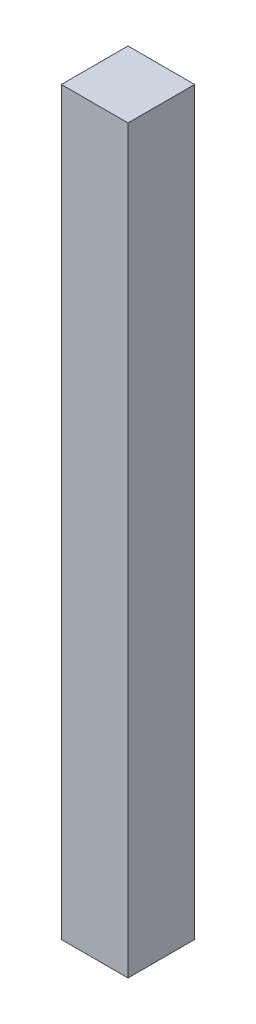
SolidWorks part; units mm, degrees
ref_plane "Front Plane" through (0, 0, 0) normal (0, 0, 1) x (1, 0, 0)
ref_plane "Top Plane" through (0, 0, 0) normal (0, 1, 0) x (1, 0, 0)
ref_plane "Right Plane" through (0, 0, 0) normal (1, 0, 0) x (0, 0, -1)
other "Configuration Table"
sketch "Sketch1" plane through (0, 0, 0) normal (0, 0, 1) x (1, 0, 0)
  line L1 (45, 770) -> (63, 770)
  line L2 (45, 770) -> (45, 970)
  line L3 (45, 970) -> (63, 970)
  line L4 (63, 770) -> (63, 970)
extrude "TOPPING_klape_kat3_gazli_amortisor_1_1" add sketch "Sketch1" along normal blind 18 from offset 8 separate body
